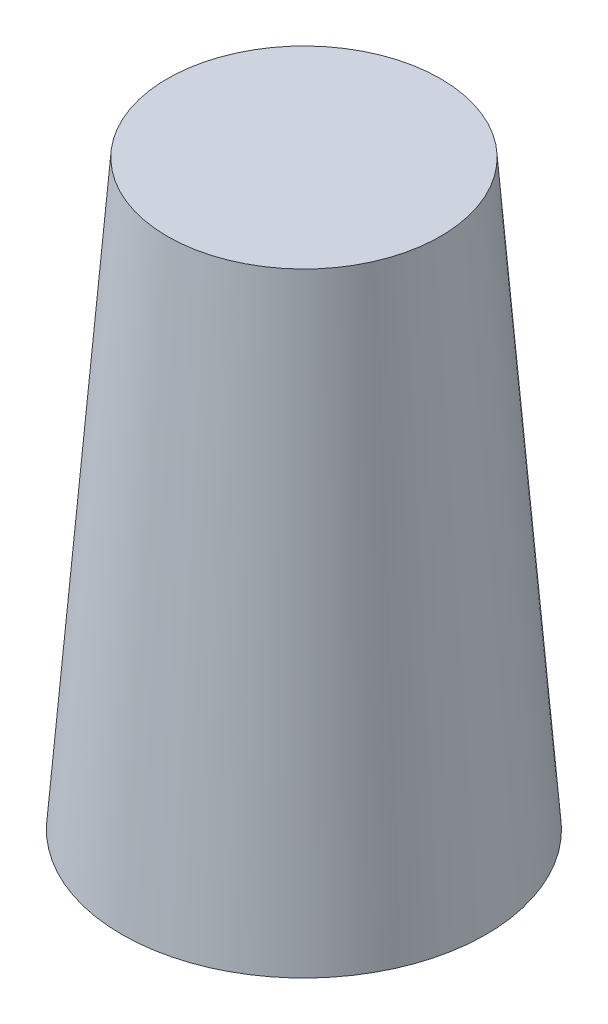
SolidWorks part; units mm, degrees
material "PP copolymère"
ref_plane "Plan de face" through (0, 0, 0) normal (0, 0, 1) x (1, 0, 0)
ref_plane "Plan de dessus" through (0, 0, 0) normal (0, 1, 0) x (1, 0, 0)
ref_plane "Plan de droite" through (0, 0, 0) normal (1, 0, 0) x (0, 0, -1)
sketch "Esquisse1" plane through (0, 0, 0) normal (0, 0, 1) x (1, 0, 0)
  line L0 (0, 115) -> (27, 115)
  line L1 (27, 115) -> (36, 0)
  line L2 (0, 115) -> (0, 0) construction
  line L3 (0, 113.5) -> (25.6128, 113.5)
  line L4 (25.6128, 113.5) -> (34.4954, 0)
  line L5 (0, 115) -> (0, 113.5)
  line L7 (36, 0) -> (34.4954, 0)
  line L8 (25.6128, 113.5) -> (34.5046, -0.117) construction
  point P2 (0, 460)
  dimension "D1" = 115
  dimension "D2" = 54
  dimension "D3" = 72
  dimension "D5" = 460
  dimension "D4" = 1.5
revolve "Révolution1" add sketch "Esquisse1" angle 360 about L2
